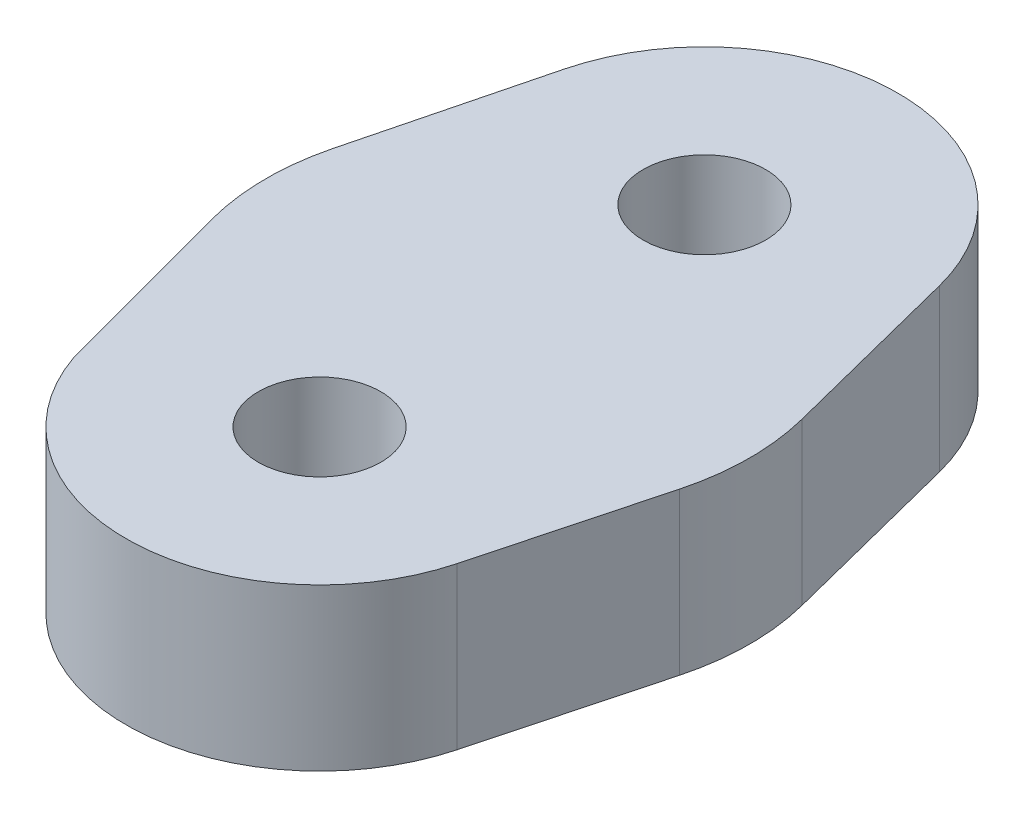
SolidWorks part; units mm, degrees
ref_plane "Front Plane" through (0, 0, 0) normal (0, 0, 1) x (1, 0, 0)
ref_plane "Top Plane" through (0, 0, 0) normal (0, 1, 0) x (1, 0, 0)
ref_plane "Right Plane" through (0, 0, 0) normal (1, 0, 0) x (0, 0, -1)
sketch "Sketch2" plane through (0, 0, 0) normal (0, 1, 0) x (1, 0, 0)
  line L0 (3.75, 7.5) -> (3.75, -7.5) construction
  line L1 (-3.4934, -1.9449) -> (-1.9217, -7.7985)
  line L2 (10.9985, -1.9261) -> (9.5488, -7.3818)
  line L3 (11.0189, 1.8474) -> (9.5651, 7.5676)
  line L4 (-2.0651, 7.5676) -> (-3.5189, 1.8474)
  circle A0 centre (7.5, 0) radius 2.5 construction
  circle A1 centre (0, 0) radius 2.5 construction
  circle A2 centre (3.75, 0) radius 7.5
  circle A3 centre (3.75, 6.0897) radius 4 construction
  circle A4 centre (3.75, -5.841) radius 4 construction
  circle A5 centre (3.75, 6.0897) radius 6
  circle A6 centre (3.75, -5.841) radius 6
  point P23 (0, 0)
  point P24 (0, 0)
  point P25 (0, 0)
  dimension "D1" = 7.5
  dimension "D2" = 5
  dimension "D4" = 15
  dimension "D5" = 12
  dimension "D6" = 12
  dimension "D7" = 8
  dimension "D8" = 8
  dimension "D3" = 3.75
  dimension "D9" = 5.841
  dimension "D10" = 6.0897
extrude "Boss-Extrude2" add sketch "Sketch2" along normal blind 5 contours A2 A6 A0 A5 A1 | A6 A2 L1 | A6 A2 A5 A0 | A6 L2 A2 | A6 A1 A5 A2 | A6 A2 L1 | A6 A0 A5 | A5 A6 | A6 A5 A1 | A6 A5 A0 A2 A1 | A2 A5 | A5 A2 L3 | A5 L4 A2
sketch "Sketch3" plane through (0, 5, 0) normal (0, 1, 0) x (1, 0, 0)
  line L0 (3.75, -11.841) -> (3.75, 12.0897) construction
  line L1 (-3.7498, -0.0504) -> (11.2499, -0.0406) construction
  circle A0 centre (3.75, -5.841) radius 4
  circle A1 centre (3.75, 6.0897) radius 4
  arc A2 (-1.9217, -7.7985) -> (9.5488, -7.3818) centre (3.75, -5.841) ccw construction
  arc A3 (9.5651, 7.5676) -> (-2.0651, 7.5676) centre (3.75, 6.0897) ccw construction
  arc A4 (-3.5189, 1.8474) -> (-3.4934, -1.9449) centre (3.75, 0) ccw construction
  arc A5 (10.9985, -1.9261) -> (11.0189, 1.8474) centre (3.75, 0) ccw construction
  dimension "D1" = 8
extrude "Boss-Extrude3" [suppressed] add sketch "Sketch3" along normal blind 22.5
sketch "Sketch4" [suppressed] plane through (0, 27.5, 0) normal (0, 1, 0) x (1, 0, 0)
  circle A0 centre (3.75, -5.841) radius 3
  circle A1 centre (3.75, 6.0897) radius 3
  circle A2 centre (3.75, -5.841) radius 4 construction
  circle A3 centre (3.75, 6.0897) radius 4 construction
  dimension "D1" = 6
  dimension "D2" = 6
extrude "Boss-Extrude4" [suppressed] add sketch "Sketch4" along normal blind 2
sketch "Sketch5" [suppressed] plane through (0, 29.5, 0) normal (0, 1, 0) x (1, 0, 0)
  circle A0 centre (3.75, -5.841) radius 4
  circle A1 centre (3.75, 6.0897) radius 4
  dimension "D1" = 8
  dimension "D2" = 8
extrude "Boss-Extrude5" [suppressed] add sketch "Sketch5" along normal blind 2
hole_wizard "#6 Clearance Hole1" positions "Sketch6" profile "Sketch7" hole size "#6" standard "ANSI Inch" end condition through all
sketch "Sketch6" plane through (0, 5, 0) normal (0, 1, 0) x (1, 0, 0)
  point P13 (3.75, 6.0897)
  point P16 (3.75, -5.841)
sketch "Sketch7" plane through (3.75, 5, -6.0897) normal (1, 0, 0) x (0, 0, 1)
  line L0 (0, 0) -> (0, 5)
  line L1 (0, 5) -> (1.8986, 5)
  line L2 (1.8986, 5) -> (1.8986, 0)
  line L5 (1.8986, 0) -> (0, 0)
  line L11 (0, -6.35) -> (0, 107.95) construction
  dimension "Thru Hole Dia." = 3.7973
  dimension "Thru Hole Depth" = 5
